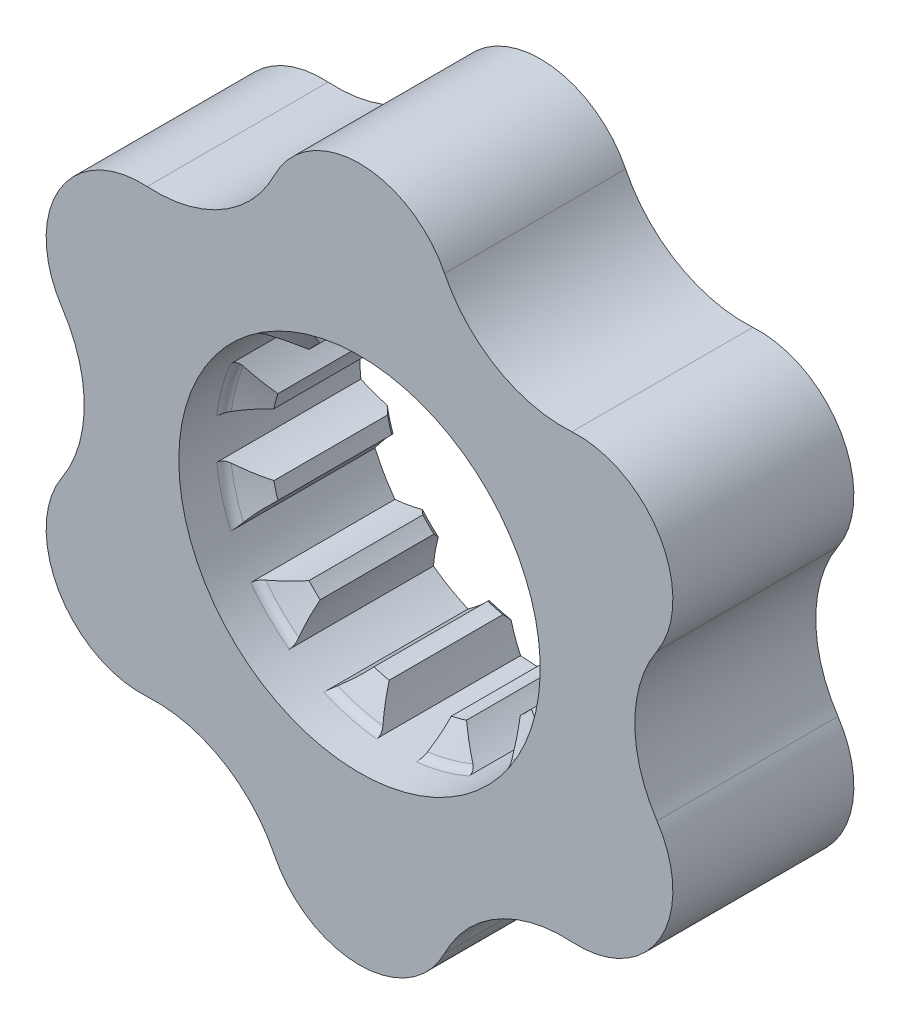
SolidWorks part; units mm, degrees
ref_plane "Front Plane" through (0, 0, 0) normal (0, 0, 1) x (1, 0, 0)
ref_plane "Top Plane" through (0, 0, 0) normal (0, 1, 0) x (1, 0, 0)
ref_plane "Right Plane" through (0, 0, 0) normal (1, 0, 0) x (0, 0, -1)
sketch "Sketch1" plane through (0, 0, 0) normal (0, 0, 1) x (1, 0, 0)
  line L0 (0, 0) -> (0, 30.3913) construction
  line L1 (0, 0) -> (36.2247, 0) construction
  line L2 (0, 0) -> (26.6587, 15.3914) construction
  line L3 (0, 0) -> (15.7458, 27.2725) construction
  circle A0 centre (0, 0) radius 26.8 construction
  circle A1 centre (0, 0) radius 21.25 construction
  circle A2 centre (0, 0) radius 11.5
  arc A3 (6.5697, 22.724) -> (-6.5697, 22.724) centre (0, 19.4675) ccw
  arc A4 (22.9644, 5.6725) -> (16.3947, 17.0515) centre (16.8593, 9.7337) ccw
  arc A5 (22.9644, -5.6725) -> (16.3947, -17.0515) centre (16.8593, -9.7337) cw
  arc A6 (6.5697, -22.724) -> (-6.5697, -22.724) centre (0, -19.4675) cw
  arc A7 (-22.9644, 5.6725) -> (-16.3947, 17.0515) centre (-16.8593, 9.7337) cw
  arc A8 (-22.9644, -5.6725) -> (-16.3947, -17.0515) centre (-16.8593, -9.7337) ccw
  arc A9 (6.5697, 22.724) -> (16.3947, 17.0515) centre (15.7458, 27.2725) ccw
  arc A10 (-6.5697, 22.724) -> (-16.3947, 17.0515) centre (-15.7458, 27.2725) cw
  arc A11 (22.9644, 5.6725) -> (22.9644, -5.6725) centre (31.4915, 0) ccw
  arc A12 (-22.9644, 5.6725) -> (-22.9644, -5.6725) centre (-31.4915, 0) cw
  arc A13 (-6.5697, -22.724) -> (-16.3947, -17.0515) centre (-15.7458, -27.2725) ccw
  arc A14 (6.5697, -22.724) -> (16.3947, -17.0515) centre (15.7458, -27.2725) cw
  dimension "D1" = 42.5
  dimension "D2" = 53.6
  dimension "D3" = 23
  dimension "D6" = 14.665
  dimension "D4" = 60
  dimension "D5" = 30
extrude "Extrude1" add sketch "Sketch1" along normal blind 13.97
sketch "Sketch4" plane through (0, 0, 0) normal (1, 0, 0) x (0, 0, -1)
  line L0 (0, 0) -> (-35.6112, 0) construction
  line L2 (0, 5.6725) -> (0, 17.0662) construction
  line L3 (0, 0) -> (-13.97, 0)
  line L4 (-0.5, 11.55) -> (-9.2844, 11.55)
  line L5 (-13.97, 11.5) -> (-13.97, -11.5) construction
  line L6 (-13.97, 13.95) -> (-13.97, 0)
  line L7 (0, 12.05) -> (0, 0)
  line L8 (0, 12.05) -> (-0.5, 11.55)
  line L10 (-13.97, 17.0662) -> (-13.97, 5.6725) construction
  line L11 (-13.97, 13.95) -> (-11.1319, 13.95)
  line L12 (-13.97, 17.0662) -> (-13.97, 5.6725) construction
  line L13 (-10.4391, 13.55) -> (-9.2844, 11.55)
  arc A0 (-11.1319, 13.95) -> (-10.4391, 13.55) centre (-11.1319, 13.15) cw
  point P8 (-10.67, 13.95)
  dimension "D5" = 0.8
  dimension "D2" = 0.5
  dimension "D3" = 45
  dimension "D4" = 23.1
  dimension "D8" = 60
  dimension "D9" = 3.3
  dimension "D10" = 27.9
revolve "Cut-Revolve1" cut sketch "Sketch4" angle 360 about L0
sketch "Sketch2" plane through (0, 0, 0) normal (0, 0, -1) x (-1, 0, 0)
  line L0 (0, 0) -> (33.1866, 0) construction
  line L1 (0, 0) -> (0, 28.3412) construction
  arc A0 (1.54, 13.8647) -> (-1.54, 13.8647) centre (0, 0) ccw
  arc A1 (-1.54, 13.8647) -> (-2.4, 11.2979) centre (9.3726, 8.7811) ccw
  arc A3 (1.54, 13.8647) -> (2.4, 11.2979) centre (-9.3726, 8.7811) cw
  arc A4 (2.4, 11.2979) -> (-2.4, 11.2979) centre (0, 0) ccw
  circle A5 centre (0, 0) radius 11.55 construction
  dimension "D1" = 27.9
  dimension "D4" = 12.0386
  dimension "D2" = 3.08
  dimension "D3" = 4.8
extrude "Extrude2" cut sketch "Sketch2" against normal up to next
pattern_circular "CirPattern1" count 12 over 360 about axis through (0, 0, 0) along (0, 0, 1) of "Extrude2"
